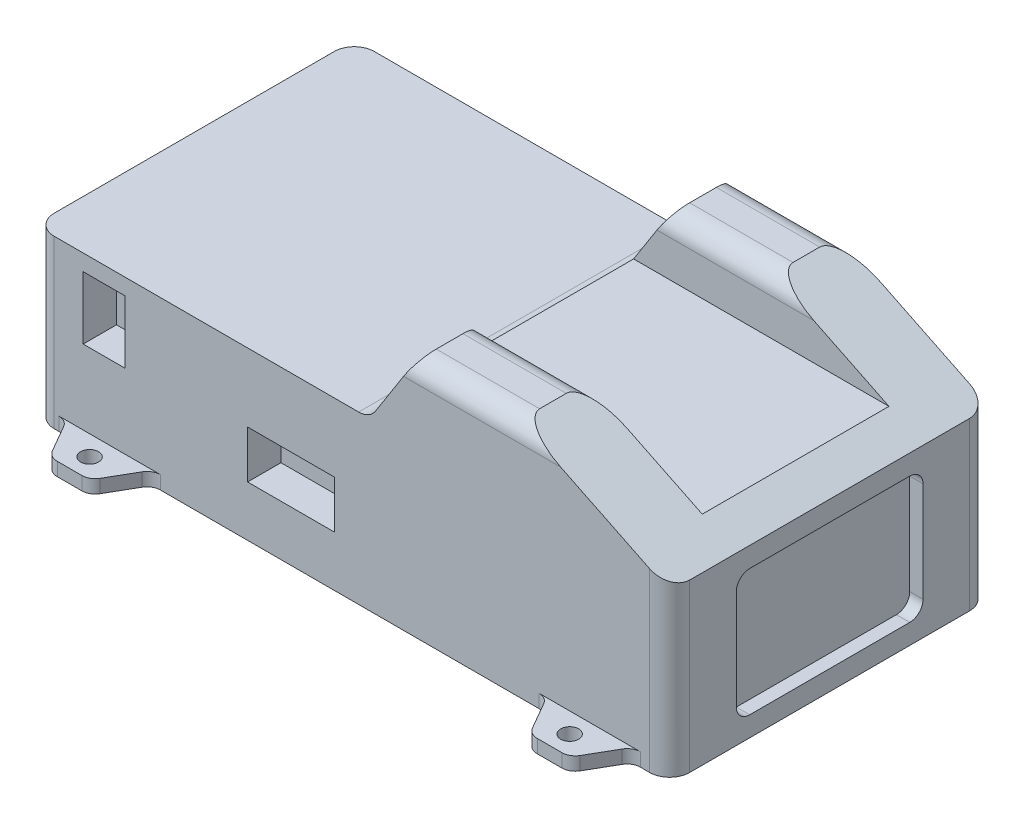
SolidWorks part; units mm, degrees
ref_plane "前视基准面" through (0, 0, 0) normal (0, 0, 1) x (1, 0, 0)
ref_plane "上视基准面" through (0, 0, 0) normal (0, 1, 0) x (1, 0, 0)
ref_plane "右视基准面" through (0, 0, 0) normal (1, 0, 0) x (0, 0, -1)
sketch "草图1" plane through (0, 0, 0) normal (0, 1, 0) x (1, 0, 0)
  line L1 (-47.65, -24) -> (47.65, -24)
  line L2 (-47.65, -24) -> (-47.65, 24)
  line L3 (-47.65, 24) -> (47.65, 24)
  line L4 (47.65, -24) -> (47.65, 24)
  line L5 (-47.65, -24) -> (47.65, 24) construction
  line L6 (-47.65, 24) -> (47.65, -24) construction
  point P0 (0, 0)
  dimension "D1" = 95.3
  dimension "D2" = 48
extrude "凸台-拉伸1" add sketch "草图1" along normal blind 25
sketch "草图2" plane through (47.65, 0, 0) normal (1, 0, 0) x (0, 0, -1)
  line L1 (-24, 25) -> (24, 25)
  line L2 (-24, 25) -> (-24, 36)
  line L3 (-24, 36) -> (-14, 36)
  line L4 (24, 25) -> (24, 36)
  line L5 (14, 36) -> (24, 36)
  line L7 (-14, 36) -> (-14, 27.5)
  line L8 (-14, 27.5) -> (14, 27.5)
  line L9 (14, 36) -> (14, 27.5)
  point P6 (0, 27.5)
  point P11 (0, 25)
  dimension "D1" = 11
  dimension "D2" = 28
  dimension "D3" = 2.5
extrude "凸台-拉伸2" add sketch "草图2" against normal blind 45
sketch "草图3" plane through (0, 0, 24) normal (0, 0, 1) x (1, 0, 0)
  line L0 (2.65, 25) -> (2.65, 36)
  line L1 (2.65, 36) -> (9.65, 36)
  line L2 (2.65, 36) -> (47.65, 36) construction
  line L3 (9.65, 36) -> (2.65, 25)
  line L4 (47.65, 25) -> (47.65, 36)
  line L5 (47.65, 36) -> (47.65, 0) construction
  line L6 (47.65, 36) -> (25.15, 36)
  line L7 (25.15, 36) -> (47.65, 25)
  dimension "D1" = 7
extrude "切除-拉伸1" cut sketch "草图3" against normal through all
sketch "草图4" plane through (47.65, 0, 0) normal (1, 0, 0) x (0, 0, -1)
  line L0 (14, 36) -> (14, 27.5) construction
  line L1 (-12, 22) -> (12, 22)
  line L2 (-14, 20) -> (-14, 5)
  line L3 (-12, 3) -> (12, 3)
  line L4 (14, 20) -> (14, 5)
  line L5 (-14, 27.5) -> (-14, 36) construction
  line L6 (-24, 0) -> (24, 0) construction
  line L7 (24, 25) -> (24, 0) construction
  arc A0 (12, 22) -> (14, 20) centre (12, 20) cw
  arc A1 (12, 3) -> (14, 5) centre (12, 5) ccw
  arc A2 (-14, 5) -> (-12, 3) centre (-12, 5) ccw
  arc A3 (-12, 22) -> (-14, 20) centre (-12, 20) ccw
  point P10 (14, 12.5)
  point P13 (24, 12.5)
  dimension "D2" = 2
  dimension "D1" = 3
extrude "切除-拉伸2" cut sketch "草图4" against normal blind 2
sketch "草图5" plane through (0, 0, 0) normal (0, -1, 0) x (1, 0, 0)
  line L0 (47.65, 24) -> (47.65, -24) construction
  line L1 (-47.65, 24) -> (47.65, 24) construction
  line L2 (29.1859, 24) -> (32.65, 30)
  line L3 (32.65, 30) -> (38.65, 30)
  line L4 (38.65, 30) -> (42.1141, 24)
  line L5 (29.1859, 24) -> (42.1141, 24)
  line L6 (-42.8141, 24) -> (-39.35, 30)
  line L7 (-39.35, 30) -> (-33.35, 30)
  line L8 (-33.35, 30) -> (-29.8859, 24)
  line L9 (-42.8141, 24) -> (-29.8859, 24)
  circle A0 centre (35.65, 27) radius 1.35
  circle A1 centre (-36.35, 27) radius 1.35
  point P10 (35.65, 30)
  point P12 (40.3821, 27)
  point P13 (30.9179, 27)
  point P20 (-36.35, 30)
  point P21 (-31.6179, 27)
  point P22 (-41.0821, 27)
  dimension "D1" = 12
  dimension "D3" = 2.7
  dimension "D6" = 2.7
  dimension "D2" = 3
  dimension "D4" = 6
  dimension "D5" = 60
  dimension "D7" = 6
  dimension "D8" = 60
  dimension "D9" = 72
extrude "凸台-拉伸3" add sketch "草图5" against normal blind 2
mirror "镜向1" about plane through (0, 0, 0) normal (0, 0, 1) of "凸台-拉伸3"
fillet "圆角1" radius 2 16 edges at (42.1141, 1, 24) (38.65, 1, 30) (32.65, 1, 30) (29.1859, 1, 24) (-29.8859, 1, 24) (-33.35, 1, 30) (-39.35, 1, 30) (-42.8141, 1, 24) (-29.8859, 1, -24) (-33.35, 1, -30) (-39.35, 1, -30) (-42.8141, 1, -24) (29.1859, 1, -24) (32.65, 1, -30) (38.65, 1, -30) (42.1141, 1, -24)
fillet "圆角2" radius 3 9 edges at (2.65, 25, 0) (17.4, 36, -24) (17.4, 36, -14) (17.4, 36, 14) (17.4, 36, 24) (47.65, 12.5, 24) (47.65, 12.5, -24) (-47.65, 12.5, 24) (-47.65, 12.5, -24)
sketch "草图6" plane through (-47.65, 0, 0) normal (-1, 0, 0) x (0, 0, 1)
  line L0 (-7, 5.783) -> (7, 5.783) construction
  circle A0 centre (-7, 5.783) radius 3.2
  circle A1 centre (7, 5.783) radius 3.2
  point P4 (0, 5.783)
  dimension "D1" = 14
  dimension "D2" = 6.4
extrude "凸台-拉伸4" add sketch "草图6" along normal blind 6
sketch "草图7" plane through (0, 0, 24) normal (0, 0, 1) x (1, 0, 0)
  line L0 (-28.7312, 0) -> (28.0312, 0) construction
  line L1 (-15.65, 14.728) -> (-2.65, 14.728)
  line L2 (-15.65, 14.728) -> (-15.65, 7.588)
  line L3 (-15.65, 7.588) -> (-2.65, 7.588)
  line L4 (-2.65, 14.728) -> (-2.65, 7.588)
  line L5 (-40.31, 22.57) -> (-34.01, 22.57)
  line L6 (-40.31, 22.57) -> (-40.31, 13.17)
  line L7 (-40.31, 13.17) -> (-34.01, 13.17)
  line L8 (-34.01, 22.57) -> (-34.01, 13.17)
  line L9 (-47.65, 0) -> (-47.65, 25) construction
  line L10 (-47.65, 0) -> (-44.65, 0) construction
  dimension "D1" = 7.14
  dimension "D2" = 7.588
  dimension "D3" = 13
  dimension "D4" = 32
  dimension "D5" = 9.4
  dimension "D6" = 6.3
  dimension "D7" = 7.34
  dimension "D8" = 13.17
extrude "切除-拉伸3" cut sketch "草图7" against normal blind 5
